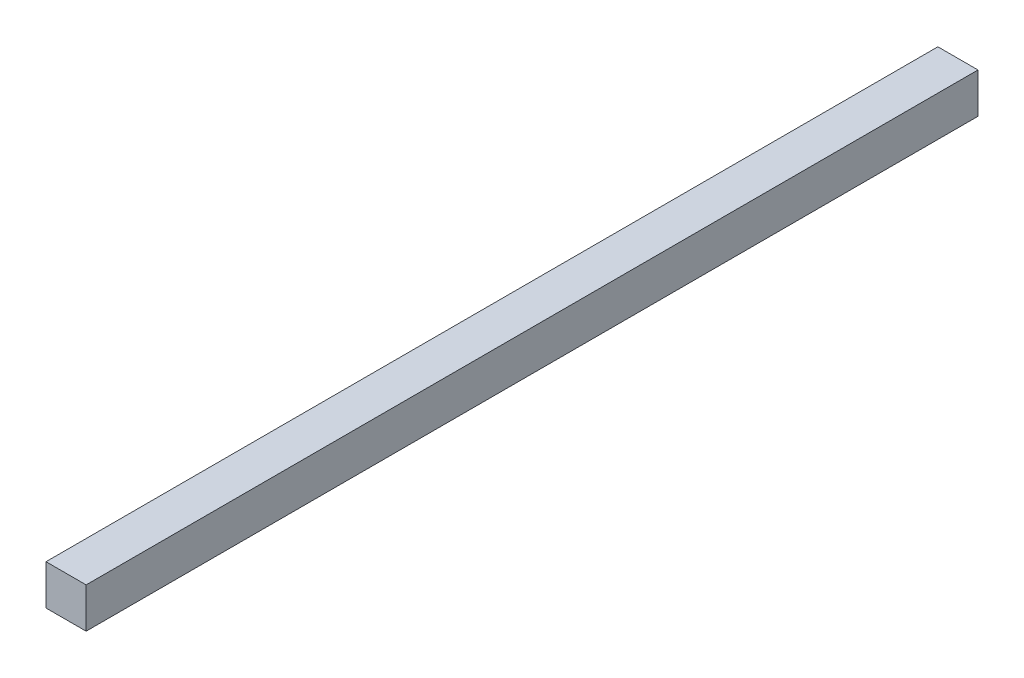
SolidWorks part; units mm, degrees
material "Pine"
ref_plane "Front Plane" through (0, 0, 0) normal (0, 0, 1) x (1, 0, 0)
ref_plane "Top Plane" through (0, 0, 0) normal (0, 1, 0) x (1, 0, 0)
ref_plane "Right Plane" through (0, 0, 0) normal (1, 0, 0) x (0, 0, -1)
sketch "Sketch1" plane through (0, 0, 0) normal (0, 0, 1) x (1, 0, 0)
  line L1 (-9, -9) -> (9, -9)
  line L2 (-9, -9) -> (-9, 9)
  line L3 (-9, 9) -> (9, 9)
  line L4 (9, -9) -> (9, 9)
  line L5 (-9, -9) -> (9, 9) construction
  line L6 (-9, 9) -> (9, -9) construction
  point P0 (0, 0)
  dimension "D1" = 18
  dimension "D2" = 18
extrude "Boss-Extrude1" add sketch "Sketch1" along normal blind 400
